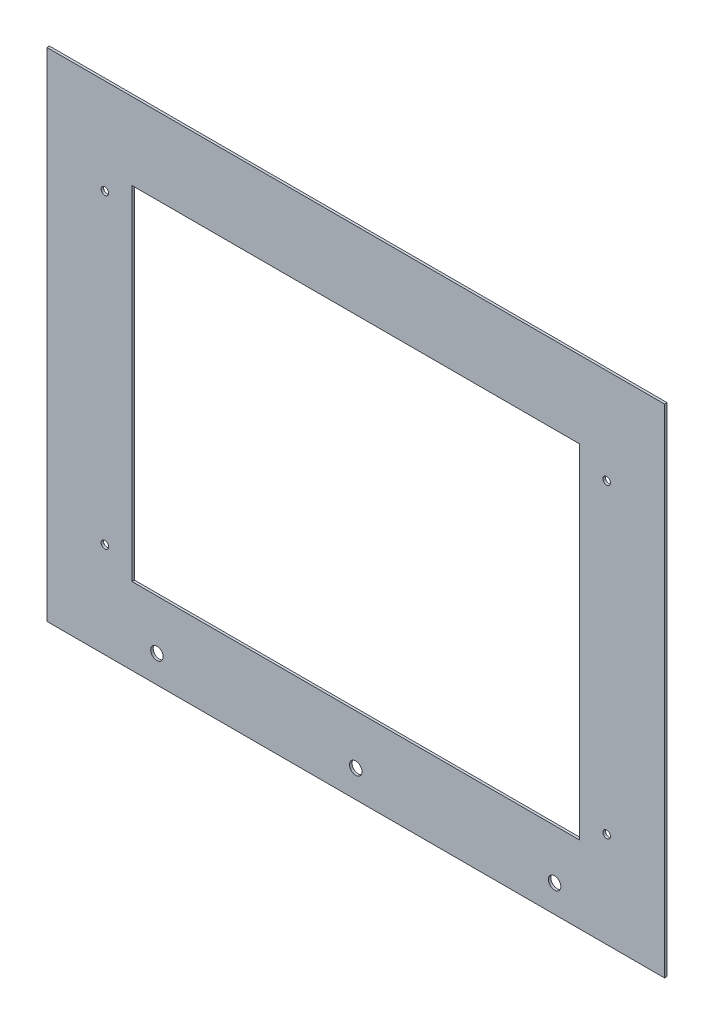
SolidWorks part; units mm, degrees
ref_plane "정면" through (0, 0, 0) normal (0, 0, 1) x (1, 0, 0)
ref_plane "윗면" through (0, 0, 0) normal (0, 1, 0) x (1, 0, 0)
ref_plane "우측면" through (0, 0, 0) normal (1, 0, 0) x (0, 0, -1)
sketch "스케치1" plane through (0, 0, 0) normal (0, 0, 1) x (1, 0, 0)
  line L0 (-64.4299, 100) -> (277.4735, 100) construction
  line L1 (0, 0) -> (248.5, 0)
  line L2 (0, 0) -> (0, 200)
  line L3 (0, 200) -> (248.5, 200)
  line L4 (248.5, 0) -> (248.5, 200)
  line L5 (33.8052, 11) -> (223.6828, 11) construction
  line L6 (124.25, 229.0993) -> (124.25, -73.1413) construction
  line L7 (225.215, 236.4085) -> (225.215, -11.9294) construction
  line L8 (34.25, 31) -> (214.25, 31)
  line L9 (34.25, 31) -> (34.25, 169)
  line L10 (34.25, 169) -> (214.25, 169)
  line L11 (214.25, 31) -> (214.25, 169)
  line L12 (250.8516, 38.405) -> (-28.7451, 38.405) construction
  circle A0 centre (124.25, 11) radius 2.5
  circle A1 centre (204.25, 11) radius 2.5
  circle A2 centre (44.25, 11) radius 2.5
  circle A3 centre (225.215, 161.595) radius 1.5
  circle A4 centre (225.215, 38.405) radius 1.5
  circle A5 centre (23.285, 38.405) radius 1.5
  circle A6 centre (23.285, 161.595) radius 1.5
  dimension "D6" = 5
  dimension "D7" = 80
  dimension "D8" = 80
  dimension "D13" = 3
  dimension "D14" = 123.19
  dimension "D1" = 248.5
  dimension "D2" = 200
  dimension "D3" = 124.25
  dimension "D4" = 100
  dimension "D5" = 11
  dimension "D9" = 138
  dimension "D10" = 180
  dimension "D11" = 90
  dimension "D12" = 69
  dimension "D15" = 61.595
  dimension "D16" = 100.965
extrude "보스-돌출1" add sketch "스케치1" along normal mid plane 1
